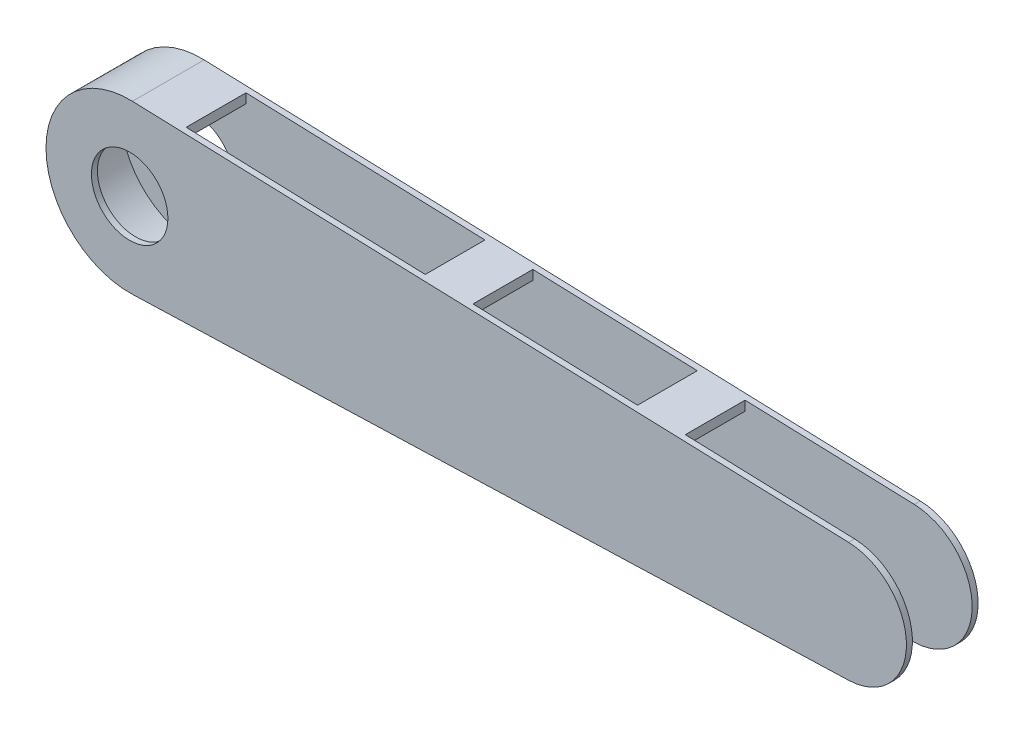
SolidWorks part; units mm, degrees
ref_plane "Спереди" through (0, 0, 0) normal (0, 0, 1) x (1, 0, 0)
ref_plane "Сверху" through (0, 0, 0) normal (0, 1, 0) x (1, 0, 0)
ref_plane "Справа" through (0, 0, 0) normal (1, 0, 0) x (0, 0, -1)
other "Configuration Table"
sketch "Эскиз1" plane through (0, 0, 0) normal (0, 0, 1) x (1, 0, 0)
  line L0 (-1000, 0) -> (49000, 0) construction
  line L1 (1.1667, 34.9806) -> (300.8333, 24.9861)
  line L2 (1.1667, -34.9806) -> (300.8333, -24.9861)
  arc A0 (1.1667, 34.9806) -> (1.1667, -34.9806) centre (0, 0) ccw
  arc A1 (300.8333, -24.9861) -> (300.8333, 24.9861) centre (300, 0) ccw
  arc A2 (300.8333, 24.9861) -> (275, 0) centre (300, 0) ccw construction
  arc A3 (275, 0) -> (300.8333, -24.9861) centre (300, 0) ccw construction
  arc A4 (35, 0) -> (1.1667, 34.9806) centre (0, 0) ccw construction
  arc A5 (1.1667, -34.9806) -> (35, 0) centre (0, 0) ccw construction
  dimension "D1" = 70
  dimension "D2" = 50
  dimension "D3" = 300
extrude "Бобышка-Вытянуть1" add sketch "Эскиз1" against normal mid plane 30
sketch "Эскиз3" plane through (0, 0, 0) normal (0, 0, 1) x (1, 0, 0)
  circle A0 centre (0, 0) radius 16 construction
  circle A1 centre (0, 0) radius 16
extrude "Вырез-Вытянуть1" cut sketch "Эскиз3" against normal through all both and the other way through all
sketch "Эскиз4" plane through (0, 0, 0) normal (0, 0, 1) x (1, 0, 0)
  line L0 (230, 23.3463) -> (210, 24.0133)
  line L1 (1.0333, -30.9828) -> (21.1667, -30.3113)
  line L2 (1.1667, -34.9806) -> (300.8333, -24.9861)
  line L3 (300.8333, 24.9861) -> (1.1667, 34.9806)
  line L4 (1.1667, -34.9806) -> (21.1667, -34.3135) construction
  line L5 (230, 27.3485) -> (210, 28.0156) construction
  line L6 (-700, 0) -> (141.1667, 0) construction
  line L7 (230, 27.3485) -> (230, 23.3463)
  line L8 (230, 23.3463) -> (230, 0) construction
  line L9 (230, -23.3463) -> (230, -27.3485)
  line L10 (230, 0) -> (230, -23.3463) construction
  line L11 (300.7, 20.9883) -> (230, 23.3463) construction
  line L12 (300.7, 20.9883) -> (1.0333, 30.9828) construction
  line L13 (230, -23.3463) -> (300.7, -20.9883) construction
  line L14 (1.0333, -30.9828) -> (300.7, -20.9883) construction
  line L15 (230, -27.3485) -> (300.8333, -24.9861)
  line L16 (1.1667, -34.9806) -> (300.8333, -24.9861) construction
  line L17 (300.8333, 24.9861) -> (230, 27.3485)
  line L18 (300.8333, 24.9861) -> (1.1667, 34.9806) construction
  line L19 (21.1667, 34.3135) -> (21.1667, 30.3113)
  line L20 (121.1667, 30.9783) -> (121.1667, 26.9761)
  line L21 (141.1667, 30.3113) -> (141.1667, 26.3091)
  line L22 (210, 28.0156) -> (210, 24.0133)
  line L23 (121.1667, 26.9761) -> (21.1667, 30.3113) construction
  line L24 (21.1667, 30.3113) -> (1.0333, 30.9828)
  line L25 (21.1667, -30.3113) -> (121.1667, -26.9761) construction
  line L26 (121.1667, -26.9761) -> (141.1667, -26.3091)
  line L27 (21.1667, -34.3135) -> (121.1667, -30.9783)
  line L28 (121.1667, -30.9783) -> (141.1667, -30.3113) construction
  line L29 (121.1667, 30.9783) -> (21.1667, 34.3135)
  line L30 (21.1667, 34.3135) -> (1.1667, 34.9806) construction
  line L31 (210, 28.0156) -> (141.1667, 30.3113)
  line L32 (141.1667, 30.3113) -> (121.1667, 30.9783) construction
  line L33 (210, 24.0133) -> (141.1667, 26.3091) construction
  line L34 (141.1667, 26.3091) -> (121.1667, 26.9761)
  line L35 (141.1667, 0) -> (210, 0) construction
  line L36 (210, 0) -> (49300, 0) construction
  line L37 (141.1667, -26.3091) -> (210, -24.0133) construction
  line L38 (210, -24.0133) -> (230, -23.3463)
  line L39 (141.1667, -30.3113) -> (210, -28.0156)
  line L40 (210, -28.0156) -> (230, -27.3485) construction
  line L41 (21.1667, 30.3113) -> (21.1667, 0) construction
  line L42 (21.1667, -30.3113) -> (21.1667, -34.3135)
  line L43 (21.1667, 0) -> (21.1667, -30.3113) construction
  line L44 (121.1667, 26.9761) -> (121.1667, 0) construction
  line L45 (121.1667, -26.9761) -> (121.1667, -30.9783)
  line L46 (121.1667, 0) -> (121.1667, -26.9761) construction
  line L47 (141.1667, 0) -> (141.1667, -26.3091) construction
  line L48 (141.1667, -26.3091) -> (141.1667, -30.3113)
  line L49 (141.1667, 26.3091) -> (141.1667, 0) construction
  line L50 (1.1667, -34.9806) -> (300.8333, -24.9861) construction
  line L51 (210, 24.0133) -> (210, 0) construction
  line L52 (210, -24.0133) -> (210, -28.0156)
  line L53 (210, 0) -> (210, -24.0133) construction
  arc A0 (1.0333, 30.9828) -> (1.0333, -30.9828) centre (0, 0) ccw
  arc A1 (300.7, -20.9883) -> (321, 0) centre (300, 0) ccw construction
  arc A2 (1.1667, 34.9806) -> (1.1667, -34.9806) centre (0, 0) ccw
  arc A3 (300.8333, -24.9861) -> (300.8333, 24.9861) centre (300, 0) ccw
  arc A4 (1.1667, 34.9806) -> (1.1667, -34.9806) centre (0, 0) ccw construction
  arc A5 (300.8333, -24.9861) -> (300.8333, 24.9861) centre (300, 0) ccw
  arc A6 (321, 0) -> (300.7, 20.9883) centre (300, 0) ccw construction
  arc A7 (300.7, -20.9883) -> (300.7, 20.9883) centre (300, 0) ccw construction
  dimension "D3" = 70
  dimension "D4" = 20
  dimension "D5" = 20
  dimension "D6" = 20
  dimension "D7" = 100
  dimension "D1" = 0
  dimension "D2" = 4
extrude "Вырез-Вытянуть2" cut sketch "Эскиз4" against normal mid plane 25
